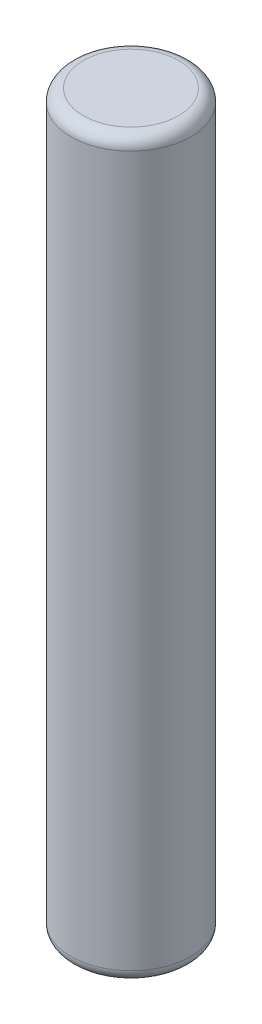
SolidWorks part; units mm, degrees
ref_plane "Front Plane" through (0, 0, 0) normal (0, 0, 1) x (1, 0, 0)
ref_plane "Top Plane" through (0, 0, 0) normal (0, 1, 0) x (1, 0, 0)
ref_plane "Right Plane" through (0, 0, 0) normal (1, 0, 0) x (0, 0, -1)
sketch "Sketch1" plane through (0, 0, 0) normal (0, 1, 0) x (1, 0, 0)
  circle A0 centre (0, 0) radius 2.45
  dimension "D1" = 4.9
extrude "Boss-Extrude1" add sketch "Sketch1" along normal blind 30
fillet "Fillet1" radius 0.5 2 edges at (0, 0, 2.45) (0, 30, 2.45)
